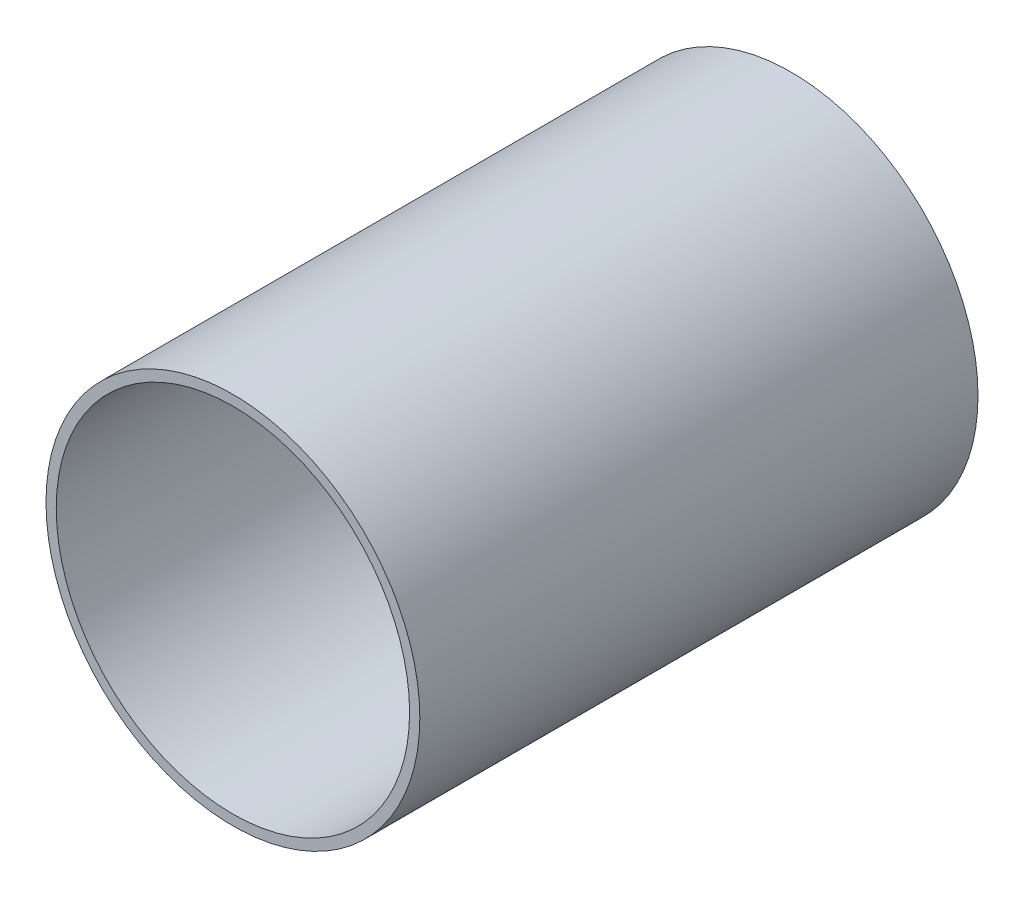
SolidWorks part; units mm, degrees
ref_plane "Plan de face" through (0, 0, 0) normal (0, 0, 1) x (1, 0, 0)
ref_plane "Plan de dessus" through (0, 0, 0) normal (0, 1, 0) x (1, 0, 0)
ref_plane "Plan de droite" through (0, 0, 0) normal (1, 0, 0) x (0, 0, -1)
sketch "Esquisse1" plane through (0, 0, 0) normal (0, 0, 1) x (1, 0, 0)
  circle A0 centre (0, 0) radius 36.5
  dimension "D1" = 73
extrude "Boss.-Extru.1" add sketch "Esquisse1" along normal blind 109
shell "Coque1" thickness 2
